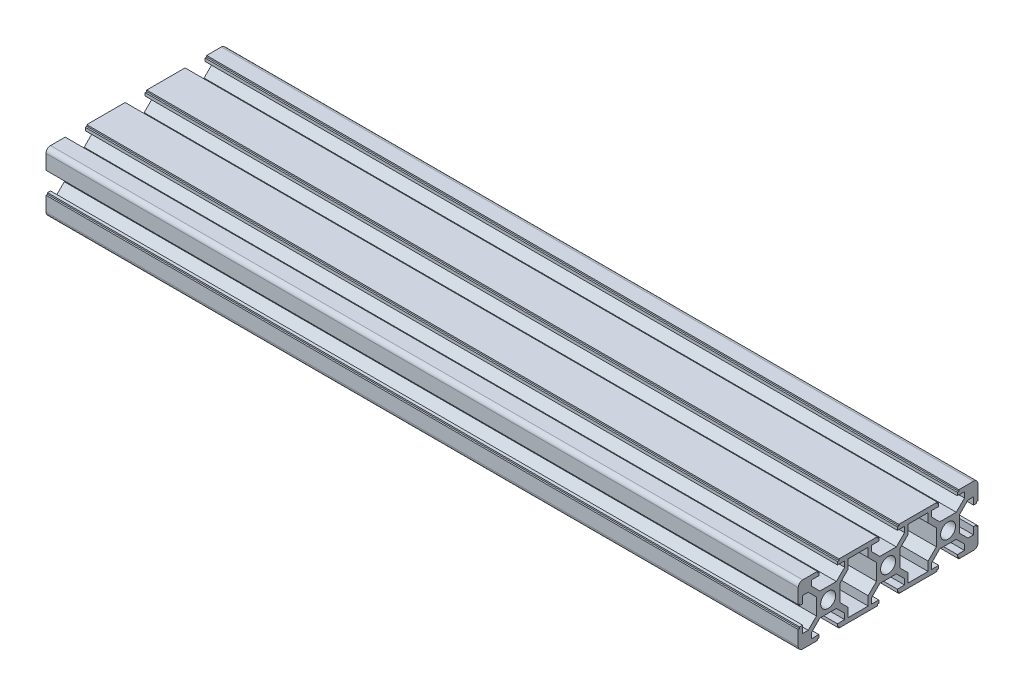
SolidWorks part; units mm, degrees
ref_plane "前视基准面" through (0, 0, 0) normal (0, 0, 1) x (1, 0, 0)
ref_plane "上视基准面" through (0, 0, 0) normal (0, 1, 0) x (1, 0, 0)
ref_plane "右视基准面" through (0, 0, 0) normal (1, 0, 0) x (0, 0, -1)
sketch "草图5" plane through (0, 0, 0) normal (0, 0, 1) x (1, 0, 0)
  line L0 (548.6373, 8.9854) -> (799.6373, 8.9854)
  dimension "D1" = 251
other "铝型材 20 X 20 X R1.5(1)"
ref_plane "基准面2" through (548.6373, 8.9854, 0) normal (1, 0, 0) x (0, 1, 0)
sketch "Sketch1" plane through (548.6373, 8.9854, 0) normal (1, 0, 0) x (0, 1, 0)
  line L0 (-10, -3.6) -> (-9.5, -3.6)
  line L1 (-9.5, -3.6) -> (-9.5, -3.1)
  line L2 (-9.5, -3.1) -> (-8.5, -3.1)
  line L3 (-8.5, -3.1) -> (-8.5, -5.5)
  line L4 (10, -8.5) -> (10, -3.6)
  line L5 (8.5, -10) -> (3.6, -10)
  line L6 (-10, 8.5) -> (-10, 3.6)
  line L7 (-10, 11.5) -> (-10, 8.5)
  line L8 (-14.8756, 0) -> (0, 0) construction
  line L9 (0, 0) -> (0, 14.1675) construction
  line L10 (-8.5, -5.5) -> (-6.65, -5.5)
  line L11 (-6.65, -5.5) -> (-3.9, -2.75)
  line L12 (-3.9, -2.75) -> (-3.9, 2.75)
  line L13 (-6.65, 5.5) -> (-3.9, 2.75)
  line L14 (-8.5, 5.5) -> (-6.65, 5.5)
  line L15 (-8.5, 3.1) -> (-8.5, 5.5)
  line L16 (-9.5, 3.1) -> (-8.5, 3.1)
  line L17 (-9.5, 3.6) -> (-9.5, 3.1)
  line L18 (-10, 3.6) -> (-9.5, 3.6)
  line L19 (-10, -3.6) -> (-10, -8.5)
  line L20 (-5.5, 6.65) -> (-8.5, 6.65)
  line L21 (-8.5, 6.65) -> (-8.5, 13.35)
  line L22 (-8.5, 13.35) -> (-5.5, 13.35)
  line L23 (-5.5, 26.65) -> (-8.5, 26.65)
  line L24 (-8.5, 26.65) -> (-8.5, 33.35)
  line L25 (-5.5, 6.65) -> (-2.75, 3.9)
  line L26 (-2.75, 3.9) -> (2.75, 3.9)
  line L27 (5.5, 6.65) -> (2.75, 3.9)
  line L28 (-8.5, 33.35) -> (-5.5, 33.35)
  line L29 (5.5, 6.65) -> (8.5, 6.65)
  line L30 (8.5, 6.65) -> (8.5, 13.35)
  line L31 (8.5, 13.35) -> (5.5, 13.35)
  line L32 (5.5, 26.65) -> (8.5, 26.65)
  line L33 (10, 3.6) -> (9.5, 3.6)
  line L34 (9.5, 3.6) -> (9.5, 3.1)
  line L35 (9.5, 3.1) -> (8.5, 3.1)
  line L36 (8.5, 3.1) -> (8.5, 5.5)
  line L37 (8.5, 5.5) -> (6.65, 5.5)
  line L38 (6.65, 5.5) -> (3.9, 2.75)
  line L39 (3.9, 2.75) -> (3.9, -2.75)
  line L40 (6.65, -5.5) -> (3.9, -2.75)
  line L41 (8.5, -5.5) -> (6.65, -5.5)
  line L42 (8.5, -3.1) -> (8.5, -5.5)
  line L43 (9.5, -3.1) -> (8.5, -3.1)
  line L44 (9.5, -3.6) -> (9.5, -3.1)
  line L45 (10, -3.6) -> (9.5, -3.6)
  line L46 (3.6, -10) -> (3.6, -9.5)
  line L47 (3.6, -9.5) -> (3.1, -9.5)
  line L48 (3.1, -9.5) -> (3.1, -8.5)
  line L49 (3.1, -8.5) -> (5.5, -8.5)
  line L50 (5.5, -8.5) -> (5.5, -6.65)
  line L51 (5.5, -6.65) -> (2.75, -3.9)
  line L52 (2.75, -3.9) -> (-2.75, -3.9)
  line L53 (-5.5, -6.65) -> (-2.75, -3.9)
  line L54 (-5.5, -8.5) -> (-5.5, -6.65)
  line L55 (-3.1, -8.5) -> (-5.5, -8.5)
  line L56 (-3.1, -9.5) -> (-3.1, -8.5)
  line L57 (-3.6, -9.5) -> (-3.1, -9.5)
  line L58 (-3.6, -10) -> (-3.6, -9.5)
  line L59 (10, 3.6) -> (10, 8.5)
  line L60 (-3.6, -10) -> (-8.5, -10)
  line L61 (-10, 31.5) -> (-10, 28.5)
  line L62 (-10, 16.4) -> (-9.5, 16.4)
  line L63 (-9.5, 16.4) -> (-9.5, 16.9)
  line L64 (-9.5, 16.9) -> (-8.5, 16.9)
  line L65 (-8.5, 16.9) -> (-8.5, 14.5)
  line L66 (10, 11.5) -> (10, 16.4)
  line L67 (10, 31.5) -> (10, 28.5)
  line L68 (-10, 28.5) -> (-10, 23.6)
  line L69 (10, 11.5) -> (10, 8.5)
  line L70 (-8.5, 14.5) -> (-6.65, 14.5)
  line L71 (-6.65, 14.5) -> (-3.9, 17.25)
  line L72 (-3.9, 17.25) -> (-3.9, 22.75)
  line L73 (-6.65, 25.5) -> (-3.9, 22.75)
  line L74 (-8.5, 25.5) -> (-6.65, 25.5)
  line L75 (-8.5, 23.1) -> (-8.5, 25.5)
  line L76 (-9.5, 23.1) -> (-8.5, 23.1)
  line L77 (-9.5, 23.6) -> (-9.5, 23.1)
  line L78 (-10, 23.6) -> (-9.5, 23.6)
  line L79 (-10, 16.4) -> (-10, 11.5)
  line L80 (8.5, 26.65) -> (8.5, 33.35)
  line L81 (8.5, 33.35) -> (5.5, 33.35)
  line L85 (-5.5, 26.65) -> (-2.75, 23.9)
  line L86 (-2.75, 23.9) -> (2.75, 23.9)
  line L87 (5.5, 26.65) -> (2.75, 23.9)
  line L93 (10, 23.6) -> (9.5, 23.6)
  line L94 (9.5, 23.6) -> (9.5, 23.1)
  line L95 (9.5, 23.1) -> (8.5, 23.1)
  line L96 (8.5, 23.1) -> (8.5, 25.5)
  line L97 (8.5, 25.5) -> (6.65, 25.5)
  line L98 (6.65, 25.5) -> (3.9, 22.75)
  line L99 (3.9, 22.75) -> (3.9, 17.25)
  line L100 (6.65, 14.5) -> (3.9, 17.25)
  line L101 (8.5, 14.5) -> (6.65, 14.5)
  line L102 (8.5, 16.9) -> (8.5, 14.5)
  line L103 (9.5, 16.9) -> (8.5, 16.9)
  line L104 (9.5, 16.4) -> (9.5, 16.9)
  line L105 (10, 16.4) -> (9.5, 16.4)
  line L111 (5.5, 13.35) -> (2.75, 16.1)
  line L112 (2.75, 16.1) -> (-2.75, 16.1)
  line L113 (-5.5, 13.35) -> (-2.75, 16.1)
  line L119 (10, 23.6) -> (10, 28.5)
  line L122 (-14.8756, 20) -> (0, 20) construction
  line L123 (0, 20) -> (0, 34.1675) construction
  line L124 (-10, 36.4) -> (-9.5, 36.4)
  line L125 (-9.5, 36.4) -> (-9.5, 36.9)
  line L126 (-9.5, 36.9) -> (-8.5, 36.9)
  line L127 (-8.5, 36.9) -> (-8.5, 34.5)
  line L128 (10, 31.5) -> (10, 36.4)
  line L130 (-10, 48.5) -> (-10, 43.6)
  line L131 (-8.5, 50) -> (-3.6, 50)
  line L132 (-8.5, 34.5) -> (-6.65, 34.5)
  line L133 (-6.65, 34.5) -> (-3.9, 37.25)
  line L134 (-3.9, 37.25) -> (-3.9, 42.75)
  line L135 (-6.65, 45.5) -> (-3.9, 42.75)
  line L136 (-8.5, 45.5) -> (-6.65, 45.5)
  line L137 (-8.5, 43.1) -> (-8.5, 45.5)
  line L138 (-9.5, 43.1) -> (-8.5, 43.1)
  line L139 (-9.5, 43.6) -> (-9.5, 43.1)
  line L140 (-10, 43.6) -> (-9.5, 43.6)
  line L141 (-10, 36.4) -> (-10, 31.5)
  line L142 (-3.6, 50) -> (-3.6, 49.5)
  line L143 (-3.6, 49.5) -> (-3.1, 49.5)
  line L144 (-3.1, 49.5) -> (-3.1, 48.5)
  line L145 (-3.1, 48.5) -> (-5.5, 48.5)
  line L146 (-5.5, 48.5) -> (-5.5, 46.65)
  line L147 (-5.5, 46.65) -> (-2.75, 43.9)
  line L148 (-2.75, 43.9) -> (2.75, 43.9)
  line L149 (5.5, 46.65) -> (2.75, 43.9)
  line L150 (5.5, 48.5) -> (5.5, 46.65)
  line L151 (3.1, 48.5) -> (5.5, 48.5)
  line L152 (3.1, 49.5) -> (3.1, 48.5)
  line L153 (3.6, 49.5) -> (3.1, 49.5)
  line L154 (3.6, 50) -> (3.6, 49.5)
  line L155 (10, 43.6) -> (9.5, 43.6)
  line L156 (9.5, 43.6) -> (9.5, 43.1)
  line L157 (9.5, 43.1) -> (8.5, 43.1)
  line L158 (8.5, 43.1) -> (8.5, 45.5)
  line L159 (8.5, 45.5) -> (6.65, 45.5)
  line L160 (6.65, 45.5) -> (3.9, 42.75)
  line L161 (3.9, 42.75) -> (3.9, 37.25)
  line L162 (6.65, 34.5) -> (3.9, 37.25)
  line L163 (8.5, 34.5) -> (6.65, 34.5)
  line L164 (8.5, 36.9) -> (8.5, 34.5)
  line L165 (9.5, 36.9) -> (8.5, 36.9)
  line L166 (9.5, 36.4) -> (9.5, 36.9)
  line L167 (10, 36.4) -> (9.5, 36.4)
  line L173 (5.5, 33.35) -> (2.75, 36.1)
  line L174 (2.75, 36.1) -> (-2.75, 36.1)
  line L175 (-5.5, 33.35) -> (-2.75, 36.1)
  line L181 (10, 43.6) -> (10, 48.5)
  line L183 (3.6, 50) -> (8.5, 50)
  line L184 (-14.8756, 40) -> (0, 40) construction
  line L185 (0, 40) -> (0, 54.1675) construction
  line L186 (-3.6, 10) -> (-8.5, 10) [skipped]
  line L187 (-3.6, 30) -> (-8.5, 30) [skipped]
  line L188 (8.5, 10) -> (3.6, 10) [skipped]
  line L189 (8.5, 30) -> (3.6, 30) [skipped]
  line L190 (-3.6, 10) -> (-3.6, 9.5) [skipped]
  line L191 (-3.6, 9.5) -> (-3.1, 9.5) [skipped]
  line L192 (-3.1, 9.5) -> (-3.1, 8.5) [skipped]
  line L193 (-3.1, 10.5) -> (-3.1, 11.5) [skipped]
  line L194 (-3.6, 10.5) -> (-3.1, 10.5) [skipped]
  line L195 (-3.6, 10) -> (-3.6, 10.5) [skipped]
  line L196 (-3.1, 11.5) -> (-5.5, 11.5) [skipped]
  line L197 (-3.1, 8.5) -> (-5.5, 8.5) [skipped]
  line L198 (-5.5, 8.5) -> (-5.5, 6.65) [skipped]
  line L199 (-5.5, 11.5) -> (-5.5, 13.35) [skipped]
  line L200 (-5.5, 31.5) -> (-5.5, 33.35) [skipped]
  line L201 (-3.1, 31.5) -> (-5.5, 31.5) [skipped]
  line L202 (-3.1, 30.5) -> (-3.1, 31.5) [skipped]
  line L203 (-3.6, 30.5) -> (-3.1, 30.5) [skipped]
  line L204 (-3.6, 30) -> (-3.6, 30.5) [skipped]
  line L205 (5.5, 8.5) -> (5.5, 6.65) [skipped]
  line L206 (3.1, 8.5) -> (5.5, 8.5) [skipped]
  line L207 (3.1, 9.5) -> (3.1, 8.5) [skipped]
  line L208 (3.6, 9.5) -> (3.1, 9.5) [skipped]
  line L209 (3.6, 10) -> (3.6, 9.5) [skipped]
  line L210 (3.6, 10) -> (3.6, 10.5) [skipped]
  line L211 (3.6, 10.5) -> (3.1, 10.5) [skipped]
  line L212 (3.1, 10.5) -> (3.1, 11.5) [skipped]
  line L213 (3.1, 11.5) -> (5.5, 11.5) [skipped]
  line L214 (5.5, 11.5) -> (5.5, 13.35) [skipped]
  line L215 (3.6, 30) -> (3.6, 30.5) [skipped]
  line L216 (3.6, 30.5) -> (3.1, 30.5) [skipped]
  line L217 (3.1, 30.5) -> (3.1, 31.5) [skipped]
  line L218 (3.1, 31.5) -> (5.5, 31.5) [skipped]
  line L219 (5.5, 31.5) -> (5.5, 33.35) [skipped]
  circle A0 centre (0, 0) radius 2.5
  arc A1 (-8.5, -10) -> (-10, -8.5) centre (-8.5, -8.5) cw
  arc A3 (10, -8.5) -> (8.5, -10) centre (8.5, -8.5) cw
  circle A5 centre (0, 20) radius 2.5
  circle A10 centre (0, 40) radius 2.5
  arc A12 (-8.5, 50) -> (-10, 48.5) centre (-8.5, 48.5) ccw
  arc A14 (10, 48.5) -> (8.5, 50) centre (8.5, 48.5) ccw
  arc A15 (-8.5, 10) -> (-10, 11.5) centre (-8.5, 11.5) cw [skipped]
  arc A16 (-8.5, 30) -> (-10, 31.5) centre (-8.5, 31.5) cw [skipped]
  arc A17 (10, 11.5) -> (8.5, 10) centre (8.5, 11.5) cw [skipped]
  arc A18 (10, 31.5) -> (8.5, 30) centre (8.5, 31.5) cw [skipped]
  point P0 (0, 0)
  point P1 (0, 10)
  point P2 (-10, 0)
  point P3 (0, 0)
  point P4 (0, 0)
  point P5 (10, -10)
  point P6 (10, 10)
  point P7 (-10, 10)
  point P8 (-10, -10)
  point P13 (0, 0)
  point P36 (-10, -10)
  point P39 (-10, 10)
  point P44 (0, 20)
  point P87 (0, 30)
  point P88 (-10, 20)
  point P89 (0, 20)
  point P90 (0, 20)
  point P91 (10, 10)
  point P92 (10, 30)
  point P93 (-10, 30)
  point P94 (-10, 10)
  point P99 (0, 20)
  point P168 (0, 40)
  point P169 (0, 50)
  point P170 (-10, 40)
  point P171 (0, 40)
  point P172 (0, 40)
  point P173 (10, 30)
  point P174 (10, 50)
  point P175 (-10, 50)
  point P176 (-10, 30)
  point P181 (0, 40)
  dimension "D1" = 11
  dimension "D3" = 6.2
  dimension "D4" = 7.2
  dimension "D5" = 6.1
  dimension "D6" = 5
  dimension "D7" = 1.5
  dimension "D8" = 45
  dimension "D9" = 0.5
  dimension "D10" = 1
  dimension "D11" = 5.5
  dimension "D12" = 3
